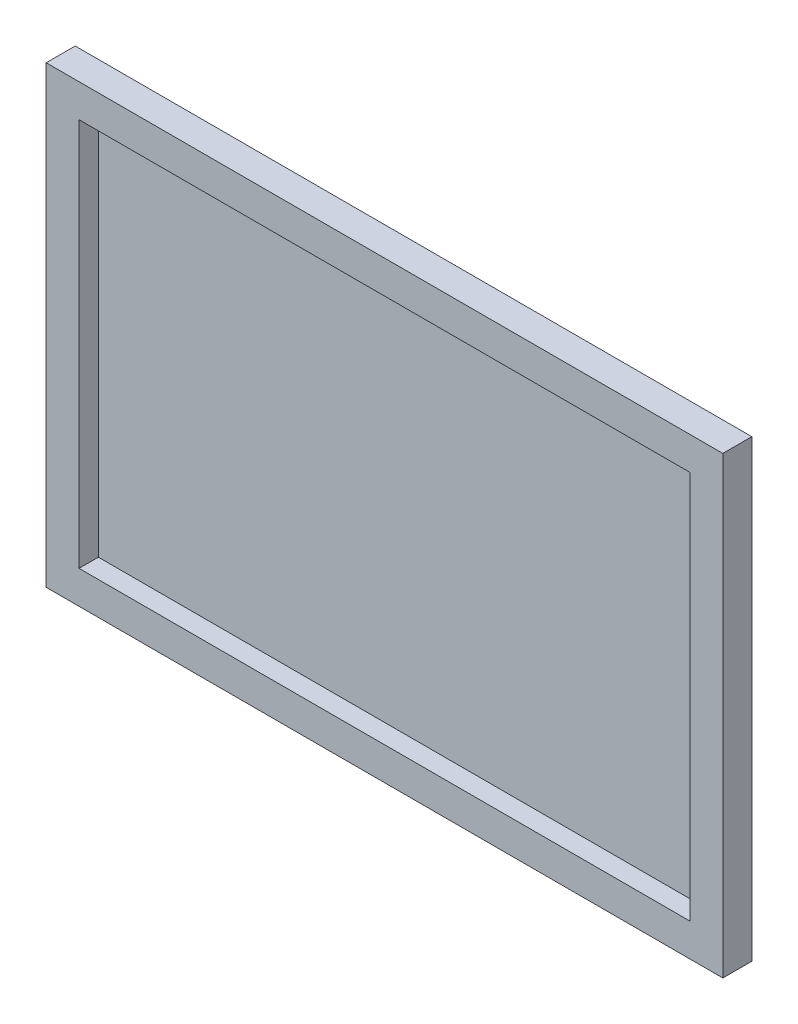
SolidWorks part; units mm, degrees
ref_plane "前视基准面" through (0, 0, 0) normal (0, 0, 1) x (1, 0, 0)
ref_plane "上视基准面" through (0, 0, 0) normal (0, 1, 0) x (1, 0, 0)
ref_plane "右视基准面" through (0, 0, 0) normal (1, 0, 0) x (0, 0, -1)
sketch "草图1" plane through (0, 0, 0) normal (0, 0, 1) x (1, 0, 0)
  line L1 (-175, 117.5) -> (175, 117.5)
  line L2 (-175, 117.5) -> (-175, -117.5)
  line L3 (-175, -117.5) -> (175, -117.5)
  line L4 (175, 117.5) -> (175, -117.5)
  line L5 (0, -117.5) -> (0, 117.5) construction
  line L6 (-175, 0) -> (175, 0) construction
  point P0 (0, 0)
  dimension "D1" = 350
  dimension "D2" = 235
extrude "凸台-拉伸1" add sketch "草图1" along normal blind 15
sketch "草图2" plane through (0, 0, 15) normal (0, 0, 1) x (1, 0, 0)
  line L0 (175, -117.5) -> (175, 117.5) construction
  line L1 (-158, 100.5) -> (158, 100.5)
  line L2 (-158, 100.5) -> (-158, -100.5)
  line L3 (-158, -100.5) -> (158, -100.5)
  line L4 (158, 100.5) -> (158, -100.5)
  line L5 (0, -100.5) -> (0, 100.5) construction
  line L6 (-158, 0) -> (158, 0) construction
  line L7 (-175, -117.5) -> (175, -117.5) construction
  point P0 (0, 0)
  dimension "D1" = 17
  dimension "D2" = 17
extrude "切除-拉伸1" cut sketch "草图2" against normal blind 10
